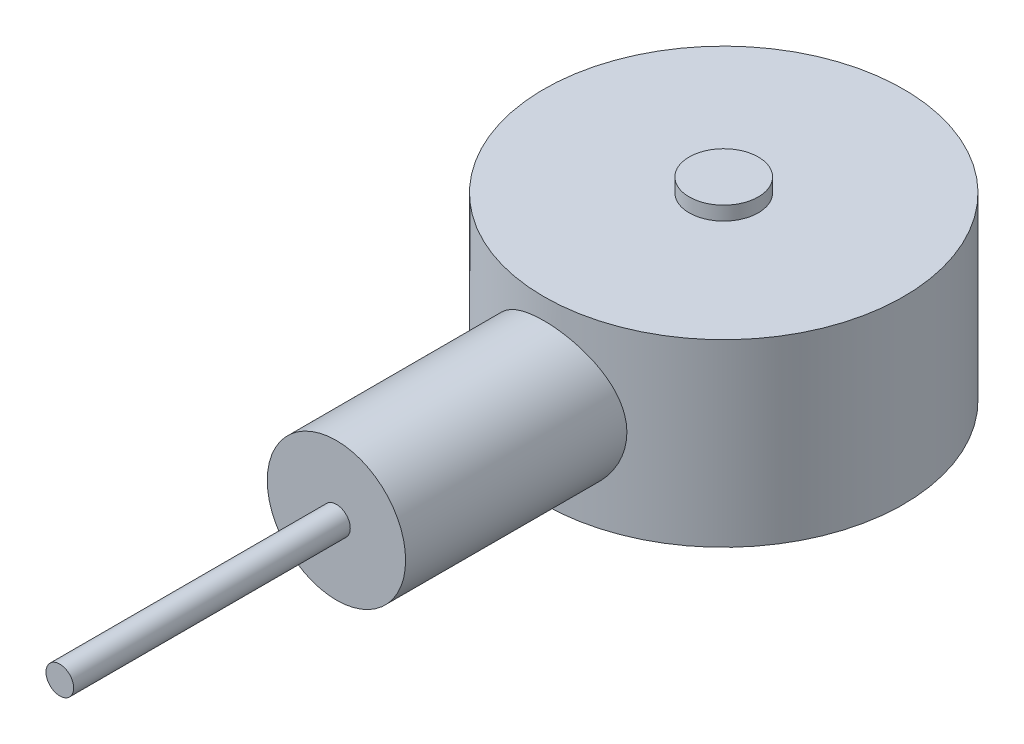
SolidWorks part; units mm, degrees
ref_plane "Front" through (0, 0, 0) normal (0, 0, 1) x (1, 0, 0)
ref_plane "Top" through (0, 0, 0) normal (0, 1, 0) x (1, 0, 0)
ref_plane "Right" through (0, 0, 0) normal (1, 0, 0) x (0, 0, -1)
sketch "Sketch1" plane through (0, 0, 0) normal (0, 1, 0) x (1, 0, 0)
  circle A0 centre (0, 0) radius 6.5
  dimension "D1" = 13
extrude "Boss-Extrude1" add sketch "Sketch1" along normal blind 6.5
sketch "Sketch2" plane through (0, 6.5, 0) normal (0, 1, 0) x (1, 0, 0)
  circle A0 centre (0, 0) radius 1.25
  dimension "D1" = 2.5
extrude "Boss-Extrude2" add sketch "Sketch2" along normal blind 0.5
sketch "Sketch4" plane through (0, 0, 0) normal (0, 0, 1) x (1, 0, 0)
  line L0 (-6.5, 0) -> (6.5, 0) construction
  circle A0 centre (0, 3.25) radius 2.5
  dimension "D1" = 5
  dimension "D2" = 3.25
extrude "Boss-Extrude4" add sketch "Sketch4" along normal blind 14
sketch "Sketch5" plane through (0, 0, 14) normal (0, 0, 1) x (1, 0, 0)
  circle A0 centre (0, 3.25) radius 0.5
  dimension "D1" = 1
extrude "Boss-Extrude5" add sketch "Sketch5" along normal blind 10
